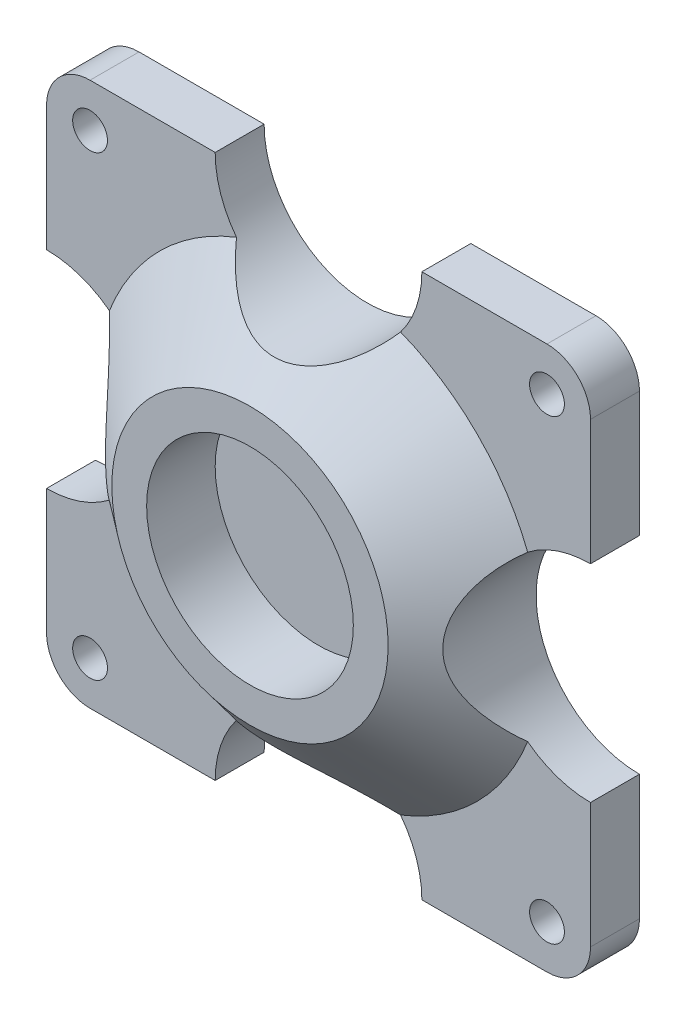
SolidWorks part; units mm, degrees
material "AISI 1035 Steel (SS)"
ref_plane "Front Plane" through (0, 0, 0) normal (0, 0, 1) x (1, 0, 0)
ref_plane "Top Plane" through (0, 0, 0) normal (0, 1, 0) x (1, 0, 0)
ref_plane "Right Plane" through (0, 0, 0) normal (1, 0, 0) x (0, 0, -1)
sketch "Sketch1" plane through (0, 0, 0) normal (0, 0, 1) x (1, 0, 0)
  line L1 (-42, 50) -> (42, 50)
  line L2 (-50, 42) -> (-50, -42)
  line L3 (-42, -50) -> (42, -50)
  line L4 (50, 42) -> (50, -42)
  line L5 (-50, 50) -> (50, -50) construction
  line L6 (-50, -50) -> (50, 50) construction
  arc A0 (-50, -42) -> (-42, -50) centre (-42, -42) ccw
  arc A1 (42, -50) -> (50, -42) centre (42, -42) ccw
  arc A2 (42, 50) -> (50, 42) centre (42, 42) cw
  arc A3 (-42, 50) -> (-50, 42) centre (-42, 42) ccw
  point P0 (0, 0)
  dimension "D2" = 8
  dimension "D1" = 100
extrude "Boss-Extrude1" add sketch "Sketch1" along normal mid plane 9
sketch "Sketch2" plane through (0, 0, 4.5) normal (0, 0, 1) x (1, 0, 0)
  circle A0 centre (0, 0) radius 41.3
  dimension "D1" = 82.6
ref_plane "Plane1" through (0, 0, 17.1) normal (0, 0, 1) x (1, 0, 0)
sketch "Sketch3" plane through (0, 0, 17.1) normal (0, 0, 1) x (1, 0, 0)
  circle A0 centre (0, 0) radius 25.4
  circle A1 centre (0, 0) radius 19
  dimension "D1" = 50.8
  dimension "D2" = 38
loft "Loft1" add profiles "Sketch2" section "Sketch2" section "Sketch3"
sketch "Sketch4" plane through (0, 0, 17.1) normal (0, 0, 1) x (1, 0, 0)
  circle A0 centre (0, 0) radius 19
  dimension "D1" = 38
extrude "Cut-Extrude1" cut sketch "Sketch4" against normal up to surface (12.6 mm away) up to face at (0, 0, 4.5)
sketch "Sketch5" plane through (0, 0, 4.5) normal (0, 0, 1) x (1, 0, 0)
  circle A0 centre (-42, 42) radius 3.2
  circle A1 centre (42, 42) radius 3.2
  dimension "D1" = 6.4
extrude "Cut-Extrude2" cut sketch "Sketch5" against normal up to surface (9 mm away) up to face at (0, 0, -4.5)
mirror "Mirror1" about plane through (0, 0, 0) normal (0, 1, 0) of "Cut-Extrude2"
sketch "Sketch6" plane through (0, 0, 4.5) normal (0, 0, 1) x (1, 0, 0)
  line L0 (-42, -50) -> (42, -50) construction
  line L1 (-19, -50) -> (19, -50)
  line L3 (4.95, 0) -> (-4.95, 0) construction
  line L4 (-19, 50) -> (19, 50)
  arc A0 (-19, -50) -> (19, -50) centre (0, -50) cw
  arc A1 (-19, 50) -> (19, 50) centre (0, 50) ccw
  point P3 (0, -50)
  point P6 (0, -31)
  dimension "D1" = 19
extrude "Cut-Extrude3" cut sketch "Sketch6" against normal through all both and the other way through all
sketch "Sketch8" plane through (0, 0, 4.5) normal (0, 0, 1) x (1, 0, 0)
  line L0 (50, -42) -> (50, 42) construction
  line L1 (50, 19) -> (50, -19)
  line L2 (19, -50) -> (42, -50) construction
  arc A0 (50, -19) -> (50, 19) centre (50, 0) cw
  point P3 (31, 0)
  point P8 (50, 0)
  point P14 (50, 0)
  dimension "D1" = 19
extrude "Cut-Extrude4" cut sketch "Sketch8" against normal through all both and the other way through all
mirror "Mirror3" about plane through (0, 0, 0) normal (1, 0, 0) of "Cut-Extrude4"
equation "\"ContrustionBaseLength\"= 100"
equation "\"D1@Sketch1\"=\"ContrustionBaseLength\""
